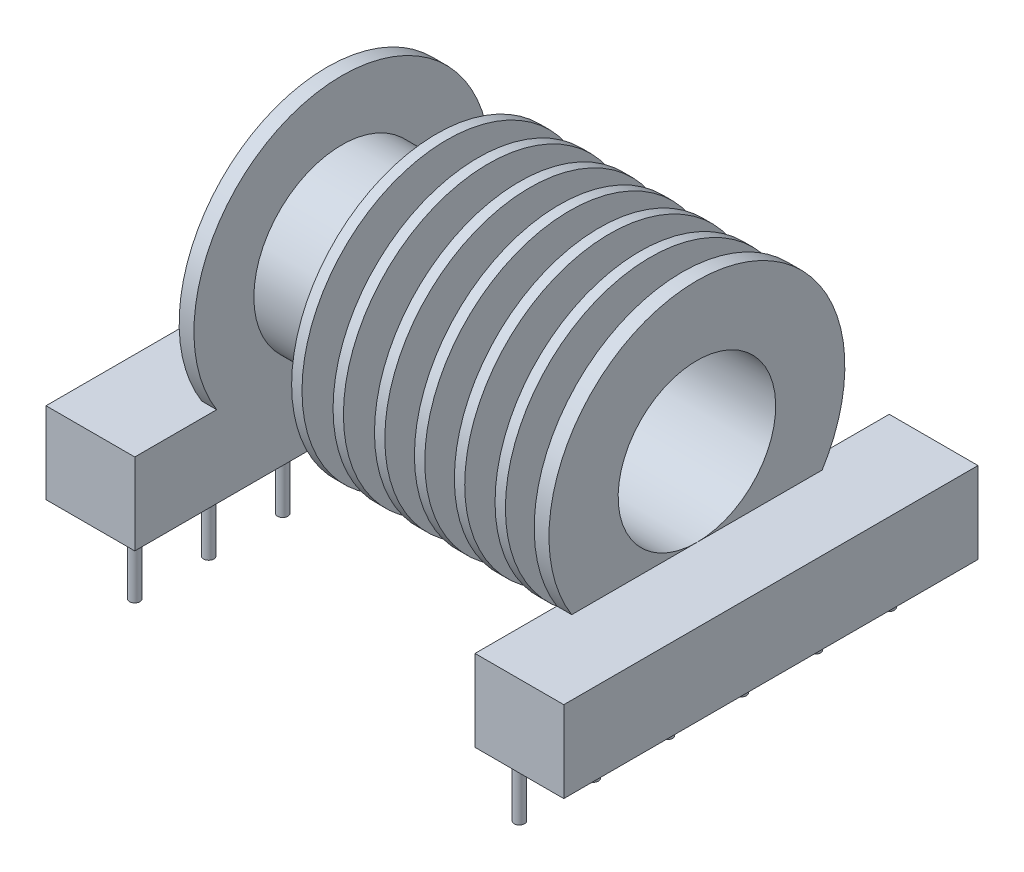
SolidWorks part; units mm, degrees
ref_plane "前视基准面" through (0, 0, 0) normal (0, 0, 1) x (1, 0, 0)
ref_plane "上视基准面" through (0, 0, 0) normal (0, 1, 0) x (1, 0, 0)
ref_plane "右视基准面" through (0, 0, 0) normal (1, 0, 0) x (0, 0, -1)
sketch "草图1" plane through (0, 0, 0) normal (0, 0, 1) x (1, 0, 0)
  line L0 (15.4385, 0) -> (-21.3685, 0) construction
  line L1 (0, 10) -> (1, 10)
  line L2 (0, 10) -> (0, 5.325)
  line L3 (0, 5.325) -> (25, 5.325)
  line L4 (25, 10) -> (25, 5.325)
  line L5 (1, 5.95) -> (24, 5.95)
  line L6 (1, 5.95) -> (1, 10)
  line L8 (24, 5.95) -> (24, 10)
  line L9 (24, 10) -> (25, 10)
  dimension "D1" = 11.9
  dimension "D2" = 10.65
  dimension "D3" = 1
  dimension "D4" = 23
  dimension "D5" = 25
  dimension "D6" = 20
revolve "旋转1" add sketch "草图1" angle 360 about L0
sketch "草图2" plane through (0, 0, 0) normal (0, 0, 1) x (1, 0, 0)
  line L1 (7.4, 5.3828) -> (8.1, 5.3828)
  line L2 (7.4, 5.3828) -> (7.4, 9.7961)
  line L3 (7.4, 9.7961) -> (8.1, 9.7961)
  line L4 (8.1, 5.3828) -> (8.1, 9.7961)
  line L5 (0, 10) -> (0, -10) construction
  line L7 (-4.3187, 0) -> (16.243, 0) construction
  line L8 (24, 10) -> (24, -10) construction
  line L9 (10.2, 5.3828) -> (10.9, 5.3828)
  line L10 (10.2, 5.3828) -> (10.2, 9.7961)
  line L11 (10.2, 9.7961) -> (10.9, 9.7961)
  line L12 (10.9, 5.3828) -> (10.9, 9.7961)
  line L13 (13, 5.3828) -> (13.7, 5.3828)
  line L14 (13, 5.3828) -> (13, 9.7961)
  line L15 (13, 9.7961) -> (13.7, 9.7961)
  line L16 (13.7, 5.3828) -> (13.7, 9.7961)
  line L17 (15.7, 5.3828) -> (16.4, 5.3828)
  line L18 (15.7, 5.3828) -> (15.7, 9.7961)
  line L19 (15.7, 9.7961) -> (16.4, 9.7961)
  line L20 (16.4, 5.3828) -> (16.4, 9.7961)
  line L21 (18.4, 5.3828) -> (19.1, 5.3828)
  line L22 (18.4, 5.3828) -> (18.4, 9.7961)
  line L23 (18.4, 9.7961) -> (19.1, 9.7961)
  line L24 (19.1, 5.3828) -> (19.1, 9.7961)
  line L25 (21.15, 5.3828) -> (21.85, 5.3828)
  line L26 (21.15, 5.3828) -> (21.15, 9.7961)
  line L27 (21.15, 9.7961) -> (21.85, 9.7961)
  line L28 (21.85, 5.3828) -> (21.85, 9.7961)
  point P4 (-8.8919, 11.7685)
  point P31 (15.7597, 9.7961)
  dimension "D1" = 8.1
  dimension "D2" = 0.7
  dimension "D3" = 10.9
  dimension "D4" = 13.7
  dimension "D5" = 21.85
  dimension "D6" = 19.1
  dimension "D7" = 16.4
  dimension "D13" = 2.15
revolve "旋转2" add sketch "草图2" angle 360 about L7
sketch "草图3" plane through (0, 0, 0) normal (0, 0, 1) x (1, 0, 0)
  line L0 (1, -10) -> (1, 10) construction
  line L1 (1, -5.325) -> (-5, -5.325)
  line L2 (1, -5.325) -> (1, -10.825)
  line L3 (1, -10.825) -> (-5, -10.825)
  line L4 (-5, -5.325) -> (-5, -10.825)
  line L5 (24, 10) -> (24, -10) construction
  line L6 (24, -5.325) -> (30, -5.325)
  line L7 (24, -5.325) -> (24, -10.825)
  line L8 (24, -10.825) -> (30, -10.825)
  line L9 (30, -5.325) -> (30, -10.825)
  line L10 (0, -5.325) -> (25, -5.325) construction
  dimension "D1" = 5.5
  dimension "D2" = 6
extrude "凸台-拉伸1" add sketch "草图3" along normal mid plane 28
sketch "草图4" plane through (0, -10.825, 0) normal (0, -1, 0) x (1, 0, 0)
  line L0 (-0.5, 12.5) -> (-0.5, 7.5) construction
  line L1 (-0.5, 7.5) -> (-0.5, 2.5) construction
  line L2 (-0.5, 2.5) -> (-0.5, -2.5) construction
  line L3 (-0.5, -2.5) -> (-0.5, -7.5) construction
  line L4 (-0.5, -7.5) -> (-0.5, -12.5) construction
  line L5 (25.5, -12.5) -> (25.5, -7.5) construction
  line L6 (25.5, -7.5) -> (25.5, -2.5) construction
  line L7 (25.5, -2.5) -> (25.5, 2.5) construction
  line L8 (25.5, 2.5) -> (25.5, 7.5) construction
  line L9 (25.5, 7.5) -> (25.5, 12.5) construction
  line L10 (2.306, 0) -> (31.0228, 0) construction
  line L11 (0, 0) -> (0, 8.4643) construction
  circle A0 centre (-0.5, 12.5) radius 0.35
  circle A1 centre (-0.5, 7.5) radius 0.35
  circle A2 centre (-0.5, 2.5) radius 0.35
  circle A3 centre (-0.5, -2.5) radius 0.35
  circle A4 centre (-0.5, -7.5) radius 0.35
  circle A5 centre (-0.5, -12.5) radius 0.35
  circle A6 centre (25.5, -12.5) radius 0.35
  circle A7 centre (25.5, -7.5) radius 0.35
  circle A8 centre (25.5, -2.5) radius 0.35
  circle A9 centre (25.5, 2.5) radius 0.35
  circle A10 centre (25.5, 7.5) radius 0.35
  circle A11 centre (25.5, 12.5) radius 0.35
  point P30 (0, 0)
  dimension "D1" = 26
  dimension "D2" = 5
  dimension "D3" = 0.5
  dimension "D4" = 0.7
extrude "凸台-拉伸2" add sketch "草图4" along normal blind 4.3
